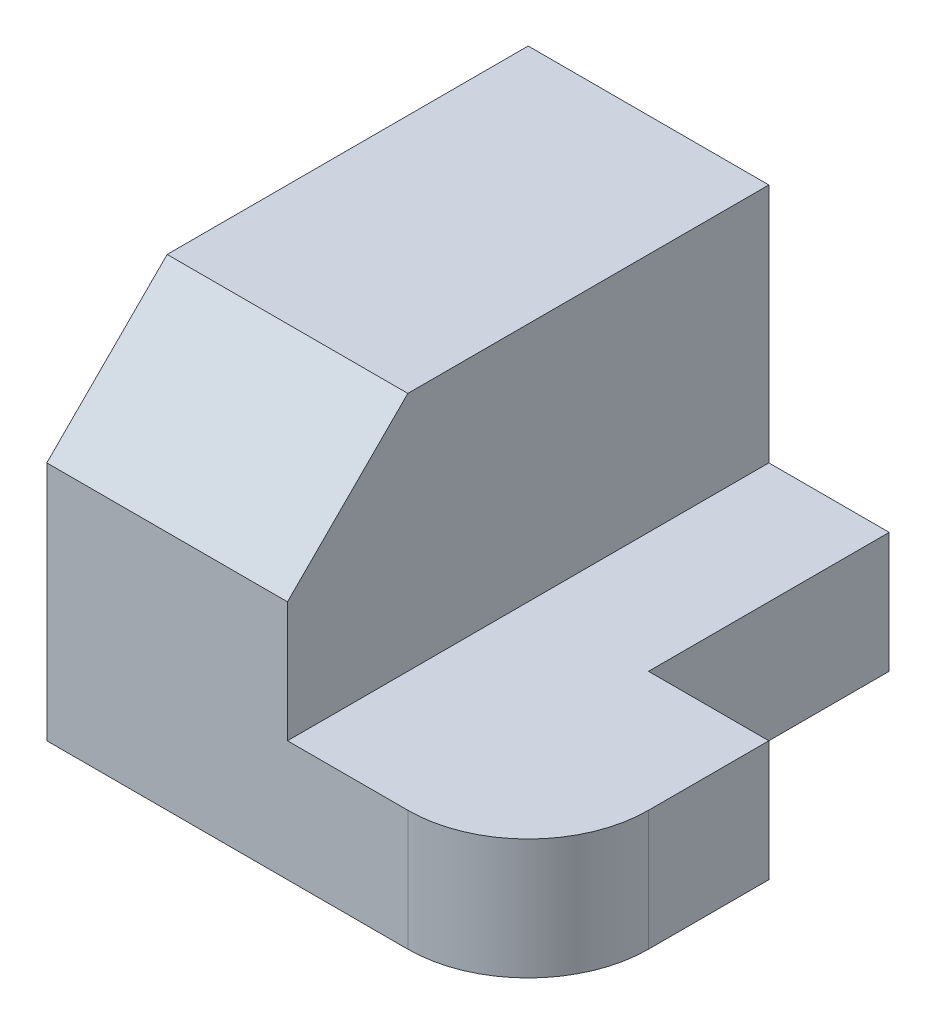
SolidWorks part; units mm, degrees
ref_plane "前基準面" through (0, 0, 0) normal (0, 0, 1) x (1, 0, 0)
ref_plane "上基準面" through (0, 0, 0) normal (0, 1, 0) x (1, 0, 0)
ref_plane "右基準面" through (0, 0, 0) normal (1, 0, 0) x (0, 0, -1)
sketch "草圖1" plane through (0, 0, 0) normal (1, 0, 0) x (0, 0, -1)
  line L0 (-20, 10) -> (-15, 15)
  line L1 (0, 0) -> (-20, 0)
  line L2 (0, 0) -> (0, 15)
  line L3 (0, 15) -> (-15, 15)
  line L4 (-20, 0) -> (-20, 10)
  point P1 (-20, 15)
  dimension "D1" = 15
  dimension "D2" = 15
extrude "填料-伸長1" add sketch "草圖1" along normal blind 10
sketch "草圖2" plane through (0, 0, 0) normal (0, 1, 0) x (1, 0, 0)
  line L1 (10, 0) -> (15, 0)
  line L2 (10, 0) -> (10, -12.0488)
  line L4 (15, 0) -> (15, -10)
  line L5 (10, -20) -> (15, -20)
  line L6 (10, -20) -> (10, -12.0488)
  line L7 (15, -10) -> (20, -10)
  line L8 (20, -15) -> (20, -10)
  arc A0 (20, -15) -> (15, -20) centre (15, -15) cw
  dimension "D1" = 5
  dimension "D2" = 5
  dimension "D3" = 10
  dimension "D4" = 5
  dimension "D5" = 10
extrude "填料-伸長2" add sketch "草圖2" along normal blind 5
